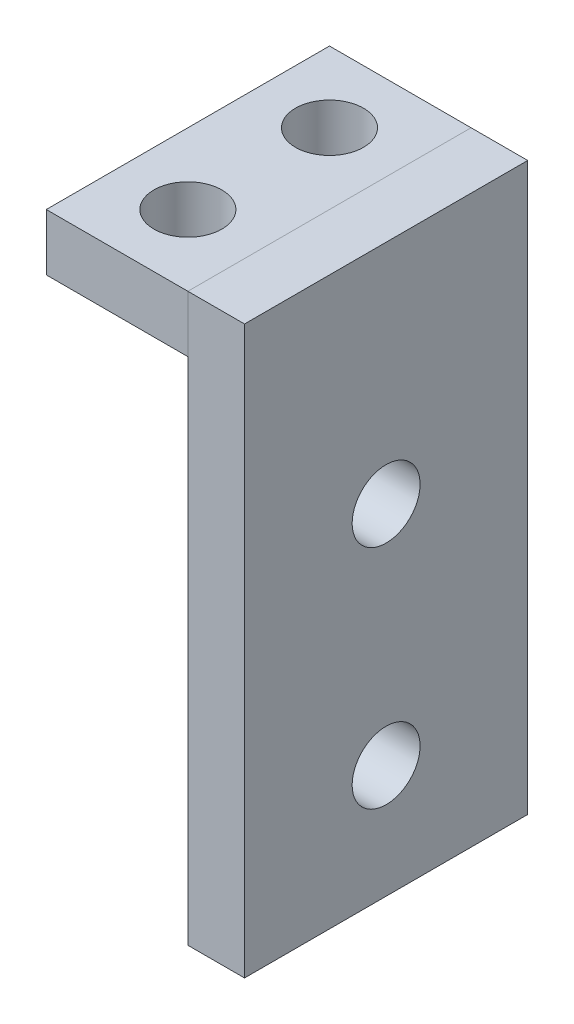
SolidWorks part; units mm, degrees
ref_plane "Front Plane" through (0, 0, 0) normal (0, 0, 1) x (1, 0, 0)
ref_plane "Top Plane" through (0, 0, 0) normal (0, 1, 0) x (1, 0, 0)
ref_plane "Right Plane" through (0, 0, 0) normal (1, 0, 0) x (0, 0, -1)
sketch "Sketch1" plane through (0, 0, 0) normal (0, 1, 0) x (1, 0, 0)
  line L1 (0, 0) -> (6.35, 0)
  line L2 (0, 0) -> (0, 12.7)
  line L3 (0, 12.7) -> (6.35, 12.7)
  line L4 (6.35, 0) -> (6.35, 12.7)
  circle A0 centre (3.175, 3.175) radius 1.524
  circle A1 centre (3.175, 9.525) radius 1.524
  dimension "D3" = 3.048
  dimension "D4" = 3.048
  dimension "D1" = 6.35
  dimension "D2" = 12.7
  dimension "D5" = 6.35
  dimension "D6" = 3.175
  dimension "D7" = 3.175
  dimension "D8" = 3.175
extrude "Boss-Extrude1" add sketch "Sketch1" along normal blind 2.54
sketch "Sketch3" plane through (0, 2.54, 0) normal (0, 1, 0) x (1, 0, 0)
  line L1 (6.35, 12.7) -> (8.89, 12.7)
  line L2 (6.35, 12.7) -> (6.35, 0)
  line L3 (6.35, 0) -> (8.89, 0)
  line L4 (8.89, 12.7) -> (8.89, 0)
  line L5 (6.35, 0) -> (6.35, 12.7) construction
  line L12 (6.35, 12.7) -> (0, 12.7) construction
  dimension "D1" = 2.54
  dimension "D2" = 12.7
extrude "Boss-Extrude3" add sketch "Sketch3" against normal blind 25.4 separate body
sketch "Sketch4" plane through (6.35, 0, 0) normal (-1, 0, 0) x (0, 0, 1)
  line L2 (0, -22.86) -> (0, 2.54) construction
  line L3 (-12.7, -22.86) -> (0, -22.86) construction
  circle A0 centre (-6.35, -7.62) radius 1.524
  circle A1 centre (-6.35, -17.78) radius 1.524
  point P4 (0, 0)
  point P5 (-6.2091, -6.062)
  dimension "D1" = 3.048
  dimension "D2" = 3.048
  dimension "D3" = 6.35
  dimension "D4" = 6.35
  dimension "D5" = 10.16
  dimension "D6" = 5.08
extrude "Cut-Extrude1" cut sketch "Sketch4" against normal through all
